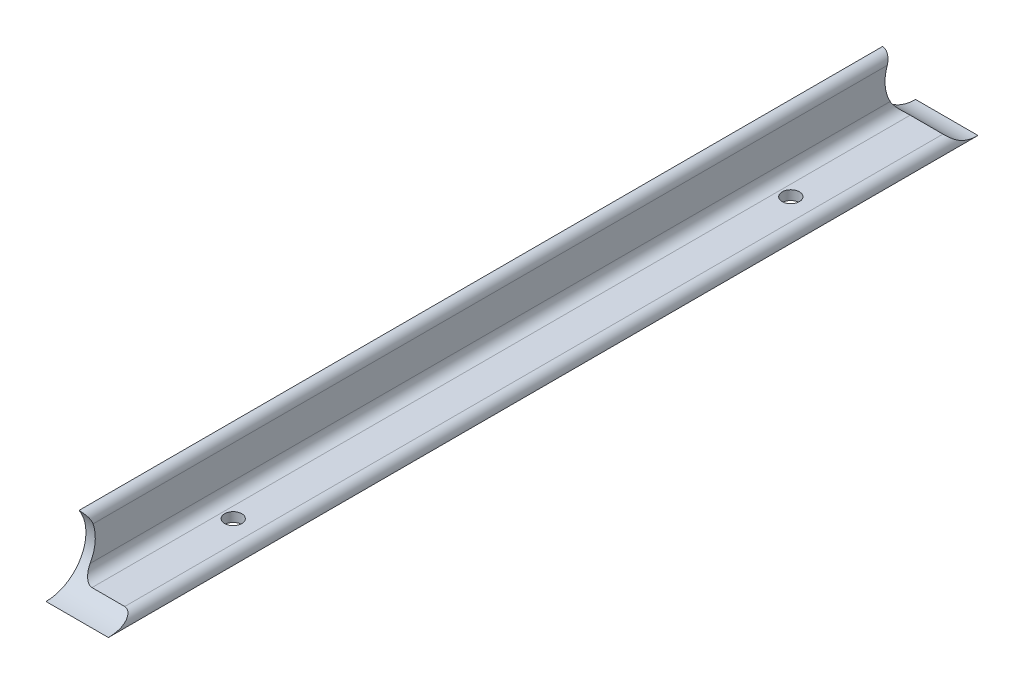
SolidWorks part; units mm, degrees
material "AISI 1010 Barra de acero laminada en caliente"
ref_plane "Alzado" through (0, 0, 0) normal (0, 0, 1) x (1, 0, 0)
ref_plane "Planta" through (0, 0, 0) normal (0, 1, 0) x (1, 0, 0)
ref_plane "Vista lateral" through (0, 0, 0) normal (1, 0, 0) x (0, 0, -1)
sketch "Croquis1" plane through (0, 0, 0) normal (0, 1, 0) x (1, 0, 0)
  line L0 (0, 97.329) -> (0, -181.371)
  dimension "D1" = 278.7
other "Miembro estructural1"
ref_plane "Plano1" through (0, 0, -97.329) normal (0, 0, 1) x (1, 0, 0)
sketch "Sketch1" plane through (0, 0, -97.329) normal (0, 0, 1) x (1, 0, 0)
  line L0 (0, 0) -> (0, 20)
  line L1 (0, 10) -> (3, 10) construction
  line L2 (3, 17) -> (3, 6.5)
  line L3 (6.5, 3) -> (17, 3)
  line L4 (10, 3) -> (10, 0) construction
  line L5 (20, 0) -> (0, 0)
  arc A0 (20, 0) -> (17, 3) centre (17, 0) ccw
  arc A1 (0, 20) -> (3, 17) centre (0, 17) cw
  arc A2 (6.5, 3) -> (3, 6.5) centre (6.5, 6.5) cw
  point P10 (10, 0)
  point P14 (0, 10)
  point P15 (3, 10)
  point P16 (10, 3)
  point P17 (3, 20)
  point P18 (20, 3)
  point P21 (0, 0)
  dimension "D2" = 3
  dimension "D3" = 20
  dimension "Radius_1" = 3.5
  dimension "D1" = 3
sketch "Croquis2" plane through (0, 0, 0) normal (1, 0, 0) x (0, 1, 0)
  line L0 (0, -97.329) -> (0, -196.9752)
  line L1 (0, -196.9752) -> (22.852, -196.9752)
  line L2 (22.852, -196.9752) -> (22.852, -180.4472)
  line L4 (22.852, -180.4472) -> (12.6952, -110.1286)
  line L5 (0, 42.021) -> (20, 42.021) construction
  line L7 (0, 181.371) -> (0, -97.329) construction
  line L8 (20, 181.371) -> (20, -97.329) construction
  line L9 (22.852, 264.4891) -> (12.6952, 194.1705)
  line L10 (22.852, 281.0172) -> (22.852, 264.4891)
  line L11 (0, 281.0172) -> (22.852, 281.0172)
  line L12 (0, 181.371) -> (0, 281.0172)
  arc A0 (0, -97.329) -> (12.6952, -110.1286) centre (12.8, -97.329) cw
  arc A1 (0, 181.371) -> (12.6952, 194.1705) centre (12.8, 181.371) ccw
  line M18 (0, 181.371) -> (20, 181.371)
  line M19 (20, 181.371) -> (20, -97.329)
  dimension "D1" = 12.8
extrude "Cortar-Extruir2" cut sketch "Croquis2" along normal through all contours A1 L9 M18 M19 | L4 A0 L0 L1 L2
hole_wizard "Taladro de margen para M51" positions "Croquis5" profile "Croquis3" hole size "M5" standard "Ansi Metric" end condition through all
sketch "Croquis5" plane through (0, 0, 0) normal (0, -1, 0) x (-1, 0, 0)
  line L0 (-10, -181.371) -> (-10, 97.329) construction
  line L1 (0, -181.371) -> (-20, -181.371) construction
  line L2 (0, 97.329) -> (-20, 97.329) construction
  point P0 (-10, -131.371)
  point P2 (-10, 47.329)
  dimension "D1" = 50
  dimension "D2" = 50
sketch "Croquis3" plane through (10, 0, 131.371) normal (1, 0, 0) x (0, 0, -1)
  line L0 (0, 0) -> (0, 20)
  line L1 (0, 20) -> (2.75, 20)
  line L2 (2.75, 20) -> (2.75, 0)
  line L5 (2.75, 0) -> (0, 0)
  line L11 (0, -6.35) -> (0, 107.95) construction
  dimension "Diámetro de taladro hasta el siguiente" = 5.5
  dimension "Profundidad de taladro hasta el siguiente" = 20
